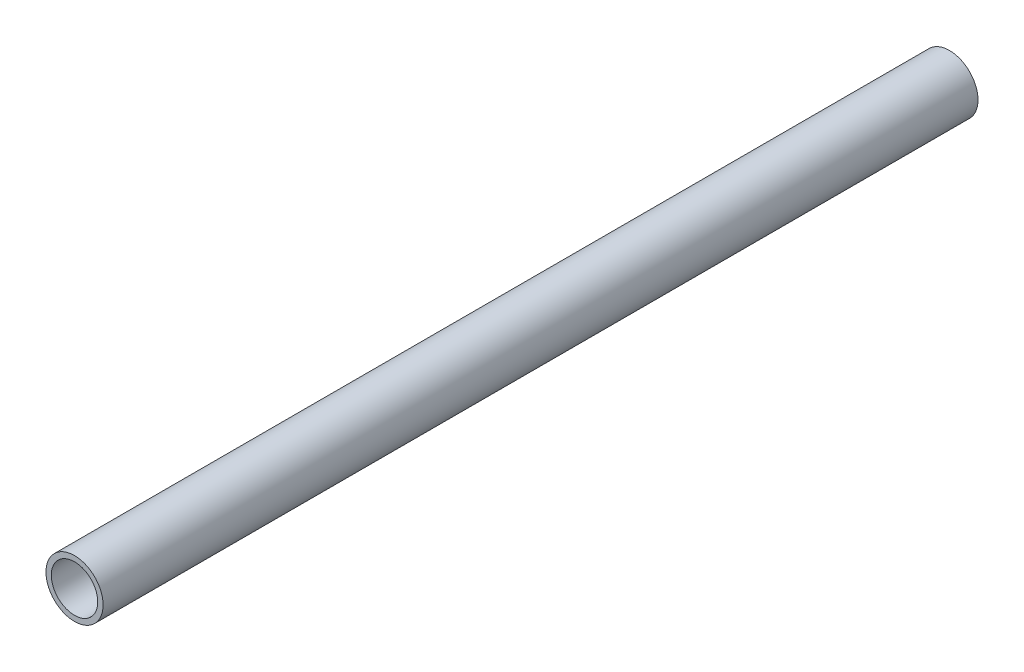
SolidWorks part; units mm, degrees
ref_plane "Alzado" through (0, 0, 0) normal (0, 0, 1) x (1, 0, 0)
ref_plane "Planta" through (0, 0, 0) normal (0, 1, 0) x (1, 0, 0)
ref_plane "Vista lateral" through (0, 0, 0) normal (1, 0, 0) x (0, 0, -1)
sketch "Croquis1" plane through (0, 0, 0) normal (0, 0, 1) x (1, 0, 0)
  circle A0 centre (0, 0) radius 16
  dimension "D1" = 32
extrude "Extruir1" add sketch "Croquis1" along normal mid plane 490
shell "Vaciado1" thickness 3
